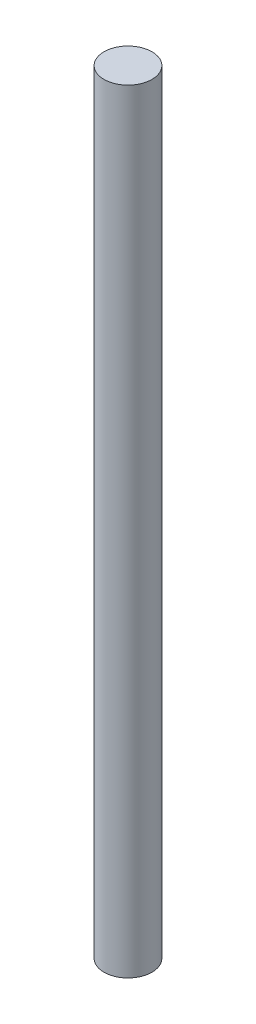
SolidWorks part; units mm, degrees
ref_plane "前视基准面" through (0, 0, 0) normal (0, 0, 1) x (1, 0, 0)
ref_plane "上视基准面" through (0, 0, 0) normal (0, 1, 0) x (1, 0, 0)
ref_plane "右视基准面" through (0, 0, 0) normal (1, 0, 0) x (0, 0, -1)
other "Configuration Table"
sketch "草图1" plane through (0, 0, 0) normal (0, 1, 0) x (1, 0, 0)
  circle A0 centre (0, 0) radius 1.55
extrude "凸台-拉伸1" add sketch "草图1" along normal blind 50
